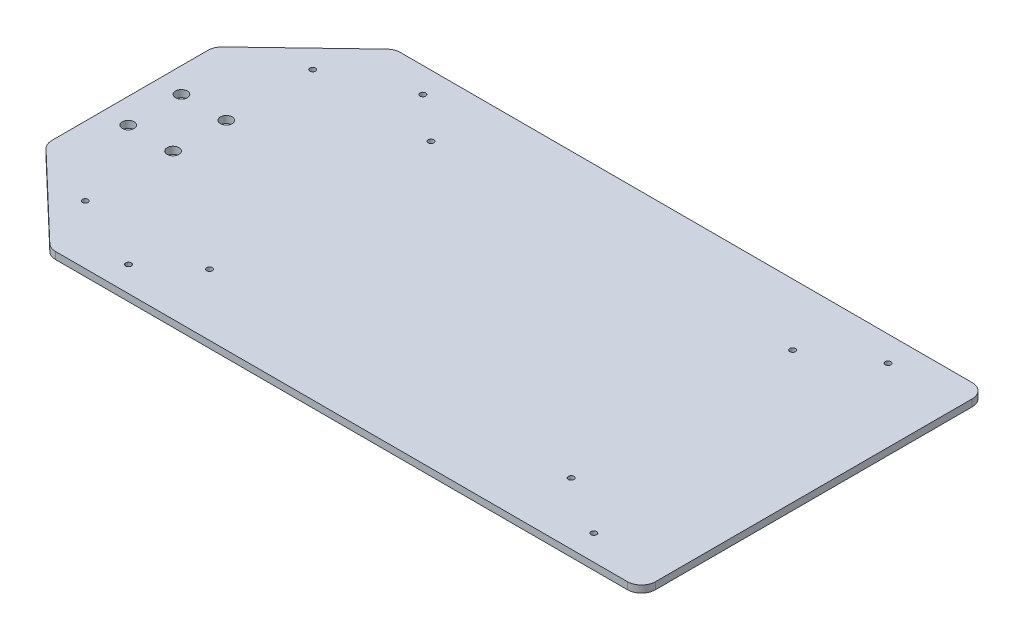
SolidWorks part; units mm, degrees
ref_plane "前视基准面" through (0, 0, 0) normal (0, 0, 1) x (1, 0, 0)
ref_plane "上视基准面" through (0, 0, 0) normal (0, 1, 0) x (1, 0, 0)
ref_plane "右视基准面" through (0, 0, 0) normal (1, 0, 0) x (0, 0, -1)
sketch "草图1" plane through (0, 0, 0) normal (0, 1, 0) x (1, 0, 0)
  line L0 (-110, 30) -> (-110, -30)
  line L1 (-110, 61.5) -> (110, 61.5)
  line L2 (-110, 61.5) -> (-110, -61.5)
  line L3 (-110, -61.5) -> (110, -61.5)
  line L4 (110, 61.5) -> (110, -61.5)
  line L7 (-110, 30) -> (-77, 61.5)
  line L8 (-110, -30) -> (-77, -61.5)
  point P0 (0, 0)
  point P6 (-77, 61.5)
  point P9 (-110, 0)
  point P10 (-77, -61.5)
  dimension "D1" = 123
  dimension "D2" = 220
  dimension "D3" = 60
  dimension "D4" = 33
  dimension "D5" = 33
extrude "凸台-拉伸2" add sketch "草图1" along normal blind 2.5 contours L0 L8 L3 L4 L1 L7
sketch "草图2" plane through (0, 2.5, 0) normal (0, 1, 0) x (1, 0, 0)
  line L0 (-110, 30) -> (-110, -30) construction
  line L1 (-110, 0) -> (-101.1032, 0)
  line L2 (-101.1032, 9.5) -> (-101.1032, -9.5)
  circle A0 centre (-101.1032, 9.5) radius 2.1
  circle A1 centre (-101.1032, -9.5) radius 2.1
  circle A2 centre (-85.1032, 9.5) radius 2.1
  circle A3 centre (-85.1032, -9.5) radius 2.1
  point P8 (-101.1032, 0)
  dimension "D3" = 4.2
  dimension "D4" = 4.2
  dimension "D1" = 8.8968
  dimension "D2" = 19
  dimension "D5" = 2
extrude "切除-拉伸1" cut sketch "草图2" against normal through all
sketch "草图3" plane through (0, 2.5, 0) normal (0, 1, 0) x (1, 0, 0)
  line L0 (-110, 0) -> (-58, 0)
  line L1 (-110, 30) -> (-110, -30) construction
  line L2 (-58, 52.5) -> (-58, -52.5)
  line L3 (108, 52.5) -> (108, -52.5)
  circle A0 centre (-58, 52.5) radius 1
  circle A1 centre (-58, -52.5) radius 1
  circle A2 centre (108, -52.5) radius 1
  circle A3 centre (108, 52.5) radius 1
  point P5 (108, 52.5)
  point P8 (-58, 0)
  dimension "D4" = 2
  dimension "D5" = 2
  dimension "D6" = 2
  dimension "D7" = 2
  dimension "D1" = 52
  dimension "D2" = 105
  dimension "D3" = 166
extrude "切除-拉伸2" cut sketch "草图3" against normal through all contours A1 | A2 | A0 | A3
sketch "草图4" plane through (0, 0, 0) normal (0, -1, 0) x (1, 0, 0)
  line L0 (-110, 0) -> (-42.0923, 0)
  line L1 (-110, -30) -> (-110, 30) construction
  line L2 (-42.0923, 39.5) -> (-42.0923, -39.5)
  line L3 (86.9077, 39.5) -> (86.9077, -39.5)
  circle A0 centre (-42.0923, 39.5) radius 1
  circle A1 centre (-42.0923, -39.5) radius 1
  circle A2 centre (86.9077, 39.5) radius 1
  circle A3 centre (86.9077, -39.5) radius 1
  point P5 (86.9077, 39.5)
  point P8 (-42.0923, 0)
  dimension "D3" = 2
  dimension "D4" = 2
  dimension "D5" = 2
  dimension "D6" = 2
  dimension "D1" = 79
  dimension "D2" = 129
extrude "切除-拉伸3" cut sketch "草图4" against normal through all contours A0 | A1 | A2 | A3
sketch "草图5" plane through (110, 0, 0) normal (1, 0, 0) x (0, 0, -1)
  line L4 (-61.5, 0) -> (61.5, 0)
  line L5 (61.5, 0) -> (61.5, 2.5)
  line L6 (61.5, 2.5) -> (-61.5, 2.5)
  line L7 (-61.5, 2.5) -> (-61.5, 0)
  line L8 (-61.5, 0) -> (61.5, 0)
  line L9 (61.5, 0) -> (61.5, 2.5)
  line L10 (61.5, 2.5) -> (-61.5, 2.5)
  line L11 (-61.5, 2.5) -> (-61.5, 0)
  dimension "D1" = 0
extrude "凸台-拉伸3" add sketch "草图5" along normal blind 24
fillet "圆角1" radius 5 6 edges at (-77, 1.25, -61.5) (-110, 1.25, -30) (-110, 1.25, 30) (-77, 1.25, 61.5) (134, 1.25, -61.5) (134, 1.25, 61.5)
sketch "草图6" plane through (0, 2.5, 0) normal (0, 1, 0) x (1, 0, 0)
  line L0 (-110, 0) -> (-85.3544, 0)
  line L1 (-110, 27.8605) -> (-110, -27.8605) construction
  line L2 (-85.3544, 40.5634) -> (-85.3544, -40.5634)
  circle A0 centre (-85.3544, 40.5634) radius 1
  circle A1 centre (-85.3544, -40.5634) radius 1
  point P9 (-85.3544, 0)
  point P10 (0, 0)
  dimension "D1" = 2
  dimension "D2" = 2
extrude "切除-拉伸4" cut sketch "草图6" against normal through all contours A0 | A1
